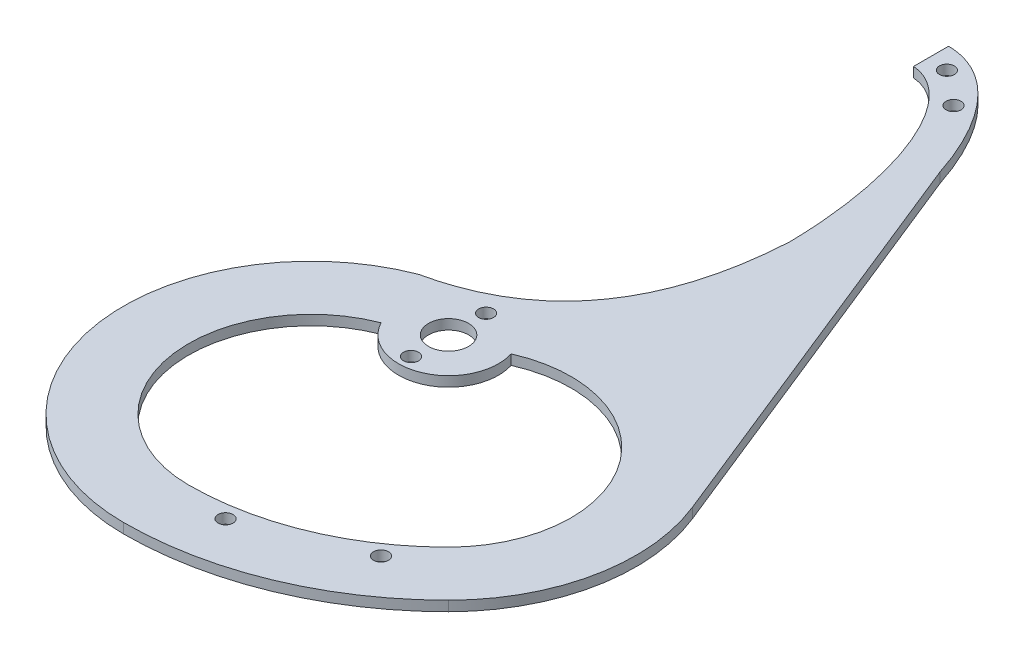
SolidWorks part; units mm, degrees
ref_plane "Спереди" through (0, 0, 0) normal (0, 0, 1) x (1, 0, 0)
ref_plane "Сверху" through (0, 0, 0) normal (0, 1, 0) x (1, 0, 0)
ref_plane "Справа" through (0, 0, 0) normal (1, 0, 0) x (0, 0, -1)
sketch "Эскиз1" plane through (0, 0, 0) normal (0, 1, 0) x (1, 0, 0)
  line L0 (0, 0) -> (0, -55) construction
  line L1 (9.5506, -54.1644) -> (0, 0) construction
  line L2 (0, 0) -> (35.7004, -86.1885) construction
  line L3 (54.236, -5.4503) -> (20.9205, 77.3689)
  line L4 (0, 0) -> (0, 100) construction
  line L5 (0, 93) -> (0, 100)
  line L7 (0, 0) -> (38.8909, -38.8909) construction
  arc A0 (45.9619, -45.9619) -> (0, -65) centre (0, 0) cw
  arc A1 (0, -52) -> (36.7696, -36.7696) centre (0, 0) ccw
  arc A2 (0, -55) -> (55, 0) centre (0, 0) ccw construction
  circle A3 centre (9.5506, -54.1644) radius 1.5
  circle A4 centre (31.5467, -45.0534) radius 1.5
  circle A5 centre (19.4454, -19.4454) radius 24.5 construction
  circle A6 centre (0, 0) radius 4
  arc A9 (-2.9671, -9.5497) -> (9.5497, 2.9671) centre (0, 0) ccw
  arc A10 (36.7696, -36.7696) -> (9.5497, 2.9671) centre (19.4454, -19.4454) ccw
  arc A11 (-13.4524, 7.504) -> (0, -65) centre (0, -27.5) ccw
  arc A12 (45.9619, -45.9619) -> (54.236, -5.4503) centre (19.4454, -19.4454) ccw
  circle A13 centre (0, 0) radius 7.5 construction
  circle A14 centre (0, -7.5) radius 1.5
  circle A15 centre (0, 7.5) radius 1.5
  circle A16 centre (0, -27.5) radius 24.5 construction
  arc A18 (0, -52) -> (-8.8507, -4.6545) centre (0, -27.5) cw
  arc A20 (-8.8507, -4.6545) -> (-2.9671, -9.5497) centre (0, 0) ccw
  ellipse E0 centre (0, 50) end of major axis (0.6457, 6.9821) minor radius 18.0072 (18.0051, 50.2703) -> (0, 93) ccw
  ellipse E3 centre (0, 50) end of major axis (0.004, 0) minor radius 25 (20.9205, 77.3689) -> (0, 100) ccw
  spline S0 degree 2 poles (-13.4524, 7.504) (16.0033, 13.8457) (18.0051, 50.2703) knots 0 0 0 1 1 1
  point P25 (-0.6653, 12.4183)
  dimension "D2" = 55
  dimension "D3" = 52
  dimension "D4" = 3
  dimension "D7" = 50
  dimension "D8" = 10
  dimension "D9" = 8
  dimension "D10" = 7
  dimension "D12" = 25
  dimension "D5" = 10
  dimension "D6" = 22.5
extrude "Бобышка-Вытянуть1" add sketch "Эскиз1" along normal blind 2
sketch "Эскиз2" plane through (0, 0, 0) normal (0, -1, 0) x (1, 0, 0)
  line L0 (0, 0) -> (0, -100) construction
  line L1 (0, -50) -> (4.795, -104.807) construction
  line L2 (0, -50) -> (14.3957, -103.7253) construction
  circle A0 centre (3.9973, -95.6893) radius 1.5
  circle A1 centre (10.7802, -90.2324) radius 1.5
  ellipse E0 centre (0, -50) end of major axis (0.004, 0) minor radius 25 (0, -100) -> (20.9205, -77.3689) ccw construction
  ellipse E1 centre (0, -50) end of major axis (0, -3.5) minor radius 21.5 construction
  dimension "D1" = 5
  dimension "D2" = 15
extrude "Вырез-Вытянуть1" cut sketch "Эскиз2" against normal through all
